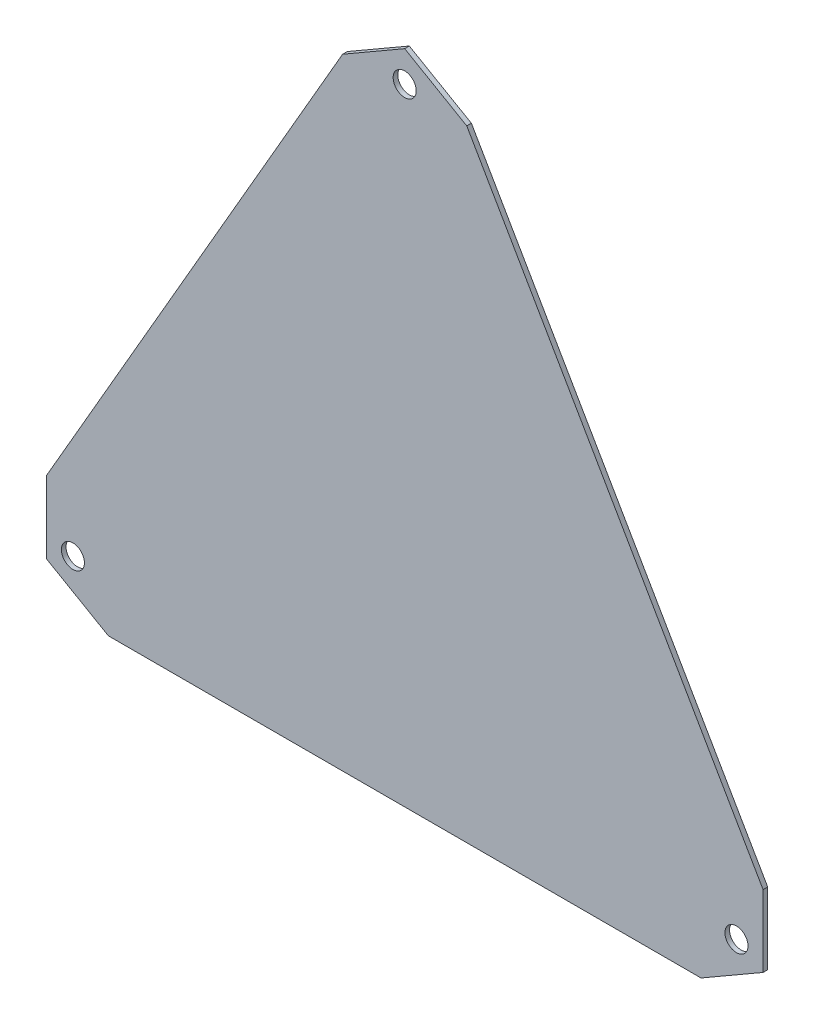
SolidWorks part; units mm, degrees
ref_plane "Plan de face" through (0, 0, 0) normal (0, 0, 1) x (1, 0, 0)
ref_plane "Plan de dessus" through (0, 0, 0) normal (0, 1, 0) x (1, 0, 0)
ref_plane "Plan de droite" through (0, 0, 0) normal (1, 0, 0) x (0, 0, -1)
sketch "Esquisse1" plane through (0, 0, 0) normal (0, 0, 1) x (1, 0, 0)
  line L0 (0, 136.0815) -> (0, 0) construction
  line L1 (0, 0) -> (117.85, -68.0407) construction
  line L2 (0, 0) -> (-117.85, -68.0407) construction
  line L3 (-77.0325, -63.1067) -> (-93.1683, -53.7907)
  line L4 (77.0325, -63.1067) -> (-77.0325, -63.1067)
  line L5 (77.0325, -63.1067) -> (93.1683, -53.7907)
  line L6 (16.1357, 98.2655) -> (93.1683, -35.1588)
  line L7 (93.1683, -35.1588) -> (93.1683, -53.7907)
  line L8 (16.1357, 98.2655) -> (0, 107.5815)
  line L9 (0, 136.0815) -> (0, 159.5946) construction
  line L10 (61, -35.2184) -> (132.0567, -76.243) construction
  line L11 (-16.1357, 98.2655) -> (0, 107.5815)
  line L12 (-93.1683, -35.1588) -> (-16.1357, 98.2655)
  line L13 (-93.1683, -35.1588) -> (-93.1683, -53.7907)
  circle A4 centre (-86.2401, -49.7907) radius 3
  circle A5 centre (0, 0) radius 99.5815 construction
  circle A6 centre (0, 99.5815) radius 3
  circle A7 centre (86.2401, -49.7907) radius 3
  point P24 (0, 0)
  point P51 (0, 0)
  dimension "D2" = 199.1629
  dimension "D3" = 8
  dimension "D6" = 8
  dimension "D7" = 6
  dimension "D8" = 3
  dimension "D9" = 6
  dimension "D10" = 6
  dimension "D4" = 120
  dimension "D5" = 120
extrude "Boss.-Extru.1" add sketch "Esquisse1" along normal blind 1.2
